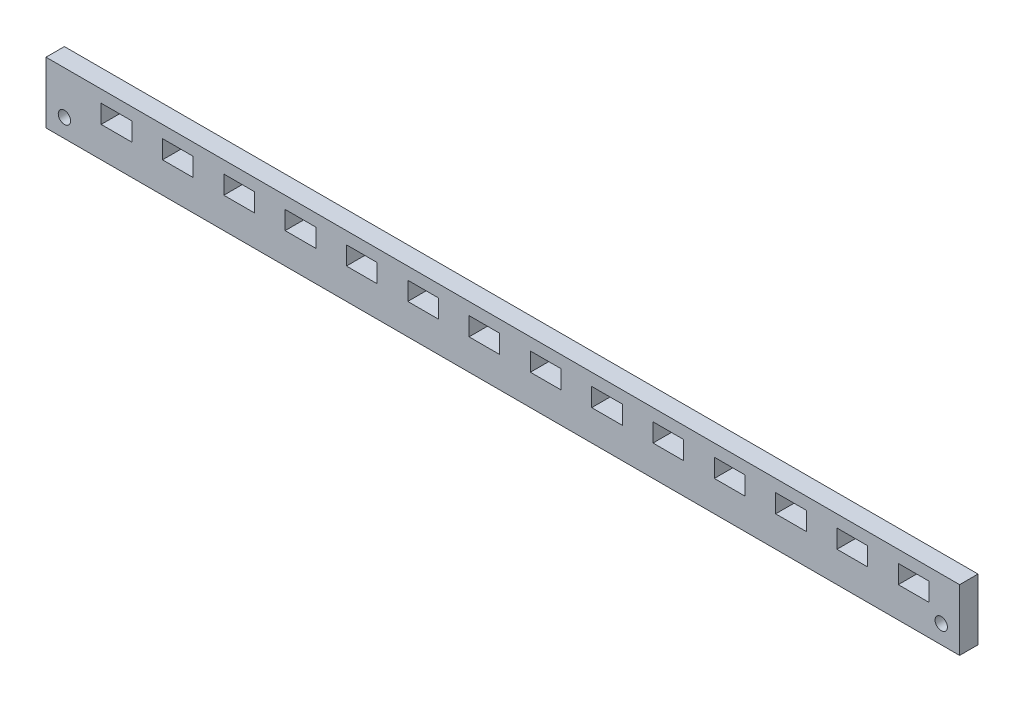
SolidWorks part; units mm, degrees
ref_plane "Plan de face" through (0, 0, 0) normal (0, 0, 1) x (1, 0, 0)
ref_plane "Plan de dessus" through (0, 0, 0) normal (0, 1, 0) x (1, 0, 0)
ref_plane "Plan de droite" through (0, 0, 0) normal (1, 0, 0) x (0, 0, -1)
sketch "Esquisse1" plane through (0, 0, 0) normal (0, 0, 1) x (1, 0, 0)
  line L1 (0, 0) -> (149, 0)
  line L2 (0, 0) -> (0, 10)
  line L3 (0, 10) -> (149, 10)
  line L4 (149, 0) -> (149, 10)
  dimension "D1" = 10
  dimension "D2" = 149
extrude "Boss.-Extru.1" add sketch "Esquisse1" along normal blind 3
sketch "Esquisse2" plane through (0, 0, 0) normal (0, 0, -1) x (-1, 0, 0)
  line L0 (0, 0) -> (-149, 0) construction
  line L1 (-149, 10) -> (0, 10) construction
  line L2 (-144, 8) -> (-139, 8)
  line L3 (-144, 8) -> (-144, 5)
  line L4 (-144, 5) -> (-139, 5)
  line L5 (-149, 0) -> (-149, 10) construction
  line L6 (0, 10) -> (0, 0) construction
  line L8 (-139, 8) -> (-139, 5)
  line L9 (-134, 8) -> (-129, 8)
  line L10 (-134, 8) -> (-134, 5)
  line L11 (-134, 5) -> (-129, 5)
  line L12 (-129, 8) -> (-129, 5)
  line L13 (-124, 8) -> (-119, 8)
  line L14 (-124, 8) -> (-124, 5)
  line L15 (-124, 5) -> (-119, 5)
  line L16 (-119, 8) -> (-119, 5)
  line L17 (-114, 8) -> (-109, 8)
  line L18 (-114, 8) -> (-114, 5)
  line L19 (-114, 5) -> (-109, 5)
  line L20 (-109, 8) -> (-109, 5)
  line L21 (-104, 8) -> (-99, 8)
  line L22 (-104, 8) -> (-104, 5)
  line L23 (-104, 5) -> (-99, 5)
  line L24 (-99, 8) -> (-99, 5)
  line L25 (-94, 8) -> (-89, 8)
  line L26 (-94, 8) -> (-94, 5)
  line L27 (-94, 5) -> (-89, 5)
  line L28 (-89, 8) -> (-89, 5)
  line L29 (-84, 8) -> (-79, 8)
  line L30 (-84, 8) -> (-84, 5)
  line L31 (-84, 5) -> (-79, 5)
  line L32 (-79, 8) -> (-79, 5)
  line L33 (-74, 8) -> (-69, 8)
  line L34 (-74, 8) -> (-74, 5)
  line L35 (-74, 5) -> (-69, 5)
  line L36 (-69, 8) -> (-69, 5)
  line L37 (-64, 8) -> (-59, 8)
  line L38 (-64, 8) -> (-64, 5)
  line L39 (-64, 5) -> (-59, 5)
  line L40 (-59, 8) -> (-59, 5)
  line L41 (-54, 8) -> (-49, 8)
  line L42 (-54, 8) -> (-54, 5)
  line L43 (-54, 5) -> (-49, 5)
  line L44 (-49, 8) -> (-49, 5)
  line L45 (-44, 8) -> (-39, 8)
  line L46 (-44, 8) -> (-44, 5)
  line L47 (-44, 5) -> (-39, 5)
  line L48 (-39, 8) -> (-39, 5)
  line L49 (-34, 8) -> (-29, 8)
  line L50 (-34, 8) -> (-34, 5)
  line L51 (-34, 5) -> (-29, 5)
  line L52 (-29, 8) -> (-29, 5)
  line L53 (-24, 8) -> (-19, 8)
  line L54 (-24, 8) -> (-24, 5)
  line L55 (-24, 5) -> (-19, 5)
  line L56 (-19, 8) -> (-19, 5)
  line L57 (-14, 8) -> (-9, 8)
  line L58 (-14, 8) -> (-14, 5)
  line L59 (-14, 5) -> (-9, 5)
  line L60 (-9, 8) -> (-9, 5)
  circle A0 centre (-3, 3) radius 1.005
  circle A1 centre (-146, 3) radius 1.005
  dimension "D1" = 2.01
  dimension "D2" = 2.01
  dimension "D3" = 3
  dimension "D4" = 3
  dimension "D5" = 5
  dimension "D6" = 3
  dimension "D9" = 3
  dimension "D13" = 3
  dimension "D7" = 5
  dimension "D8" = 2
  dimension "D10" = 14
  dimension "D11" = 2
  dimension "D12" = 5
extrude "Enlèv. mat.-Extru.1" cut sketch "Esquisse2" against normal through all
